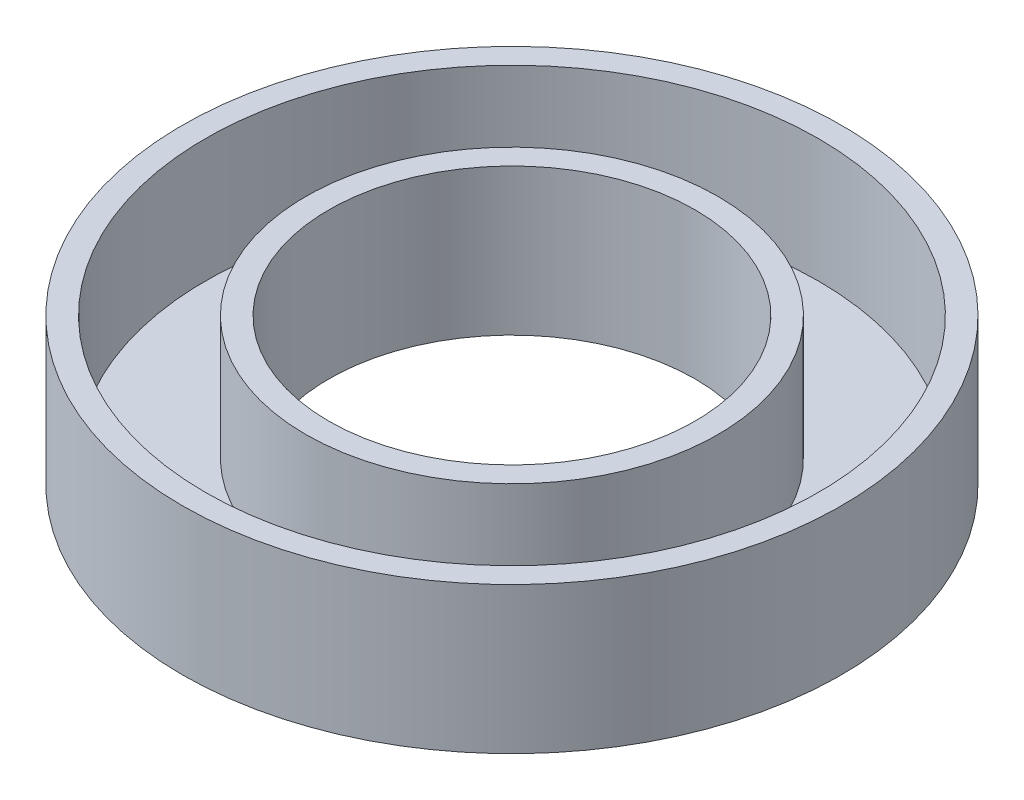
SolidWorks part; units mm, degrees
material "VITON"
ref_plane "Front Plane" through (0, 0, 0) normal (0, 0, 1) x (1, 0, 0)
ref_plane "Top Plane" through (0, 0, 0) normal (0, 1, 0) x (1, 0, 0)
ref_plane "Right Plane" through (0, 0, 0) normal (1, 0, 0) x (0, 0, -1)
sketch "Sketch1" plane through (0, 0, 0) normal (0, 1, 0) x (1, 0, 0)
  circle A0 centre (0, 0) radius 14.2875
  dimension "D1" = 28.575
extrude "main extrusion" add sketch "Sketch1" along normal blind 6.35 contours A0
sketch "Sketch2" plane through (0, 6.35, 0) normal (0, 1, 0) x (1, 0, 0)
  circle A0 centre (0, 0) radius 7.9375
  dimension "D1" = 15.875
extrude "ID bore" cut sketch "Sketch2" against normal blind 20
sketch "Sketch3" plane through (0, 6.35, 0) normal (0, 1, 0) x (1, 0, 0)
  circle A0 centre (0, 0) radius 13.2875
  circle A1 centre (0, 0) radius 8.9375
  dimension "D1" = 17.875
  dimension "D2" = 26.575
extrude "seal recess" cut sketch "Sketch3" against normal blind 5.35
equation "\"D1@Sketch1\" = \"upper seal OD\""
equation "\"D1@main extrusion\" = \"upper seal depth\""
equation "\"D1@Sketch2\" = \"upper seal ID\""
equation "\"motor mount pattern diameter\"= 30mm"
equation "\"D2@Sketch3\" = \"upper seal OD\" - 2mm"
equation "\"D1@Sketch3\" = \"upper seal ID\" + 2mm"
equation "\"D1@seal recess\" = \"upper seal depth\" - 1mm"
equation "\"upper seal OD\" = 1.125in\t'this is https://www.mcmaster.com/#5154t33/=173zuau, needs to be visually inspected before machining!"
equation "\"upper seal ID\"= 0.625in"
equation "\"upper seal depth\"= .25in\t'aka height; these values need to be confirmed by inspection!! We may want to compress the height."
equation "\"upper seal bore\" = \"upper seal depth\" + 1mm"
equation "\"upper seal plate lip ID\" = \"upper seal OD\" - 3mm"
